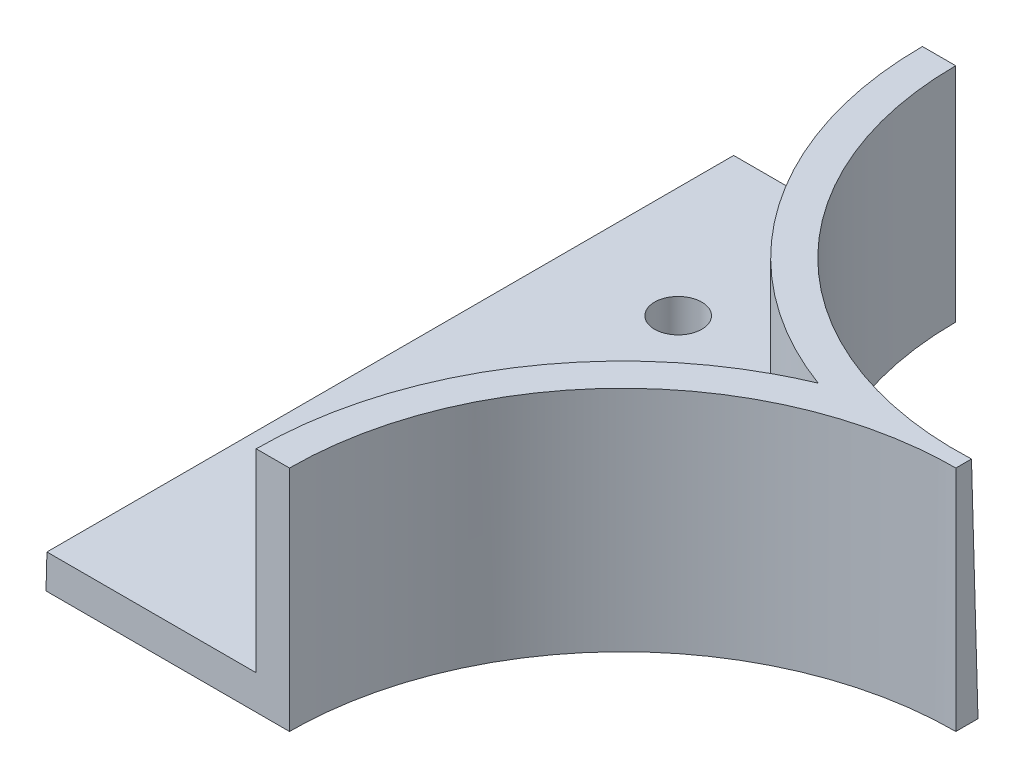
SolidWorks part; units mm, degrees
ref_plane "前基準面" through (0, 0, 0) normal (0, 0, 1) x (1, 0, 0)
ref_plane "上基準面" through (0, 0, 0) normal (0, 1, 0) x (1, 0, 0)
ref_plane "右基準面" through (0, 0, 0) normal (1, 0, 0) x (0, 0, -1)
sketch "草圖1" plane through (0, 0, 0) normal (0, 1, 0) x (1, 0, 0)
  line L0 (0, -55) -> (0, 55) construction
  line L1 (0, 30) -> (50, 30)
  line L2 (0, 30) -> (0, -30)
  line L3 (0, -30) -> (50, -30)
  line L4 (50, 30) -> (50, -30)
  line L5 (-55, 0) -> (55, 0) construction
  dimension "D1" = 50
  dimension "D2" = 60
  dimension "D3" = 30
extrude "填料-伸長1" add sketch "草圖1" along normal blind 70
draft "拔模1" type of draft neutral plane draft angle 1.591 faces to draft 2 face at (50, 35, 0) face at (25, 35, 30) neutral plane through (0, 70, 0) neutral plane normal (0, 1, 0) parameters "D1"=1.591
ref_plane "平面2" through (50, 70, 30) normal (0.0278, -0.9992, 0.0278) x (-0.9996, -0.0277, 0.0008)
sketch "草圖3" plane through (50, 70, 30) normal (0.0278, -0.9992, 0.0278) x (0.9996, 0.0277, -0.0008)
  circle A0 centre (0, 0) radius 30
extrude "除料-伸長1" cut sketch "草圖3" along normal blind 72 and the other way blind 2
sketch "草圖4" plane through (0, 70, 0) normal (0, 1, 0) x (1, 0, 0)
  circle A0 centre (50, 30) radius 30
extrude "除料-伸長2" cut sketch "草圖4" against normal blind 70
sketch "草圖5" plane through (0, 0, 0) normal (-1, 0, 0) x (0, 0, 1)
  line L0 (30, 70) -> (31.9443, 0) construction
  line L1 (-30, 70) -> (31.3888, 70)
  line L2 (-30, 70) -> (-30, 20)
  line L3 (-30, 20) -> (31.3888, 20)
  line L4 (31.3888, 70) -> (31.3888, 20)
  line L5 (44, 0) -> (-44, 0) construction
  dimension "D1" = 20
extrude "除料-伸長3" cut sketch "草圖5" against normal through all
shell "薄殼1" thickness 3
sketch "草圖6" plane through (0, 3, 0) normal (0, 1, 0) x (1, 0, 0)
  line L0 (0, 30) -> (0, -31.8609) construction
  line L1 (-11, 0) -> (11, 0) construction
  circle A0 centre (10, 15) radius 2.125
  circle A1 centre (10, -15) radius 2.125
  point P2 (0, 0)
  point P5 (0, 18.0983)
  dimension "D1" = 4.25
  dimension "D2" = 15
  dimension "D3" = 10
extrude "除料-伸長4" cut sketch "草圖6" against normal through all
